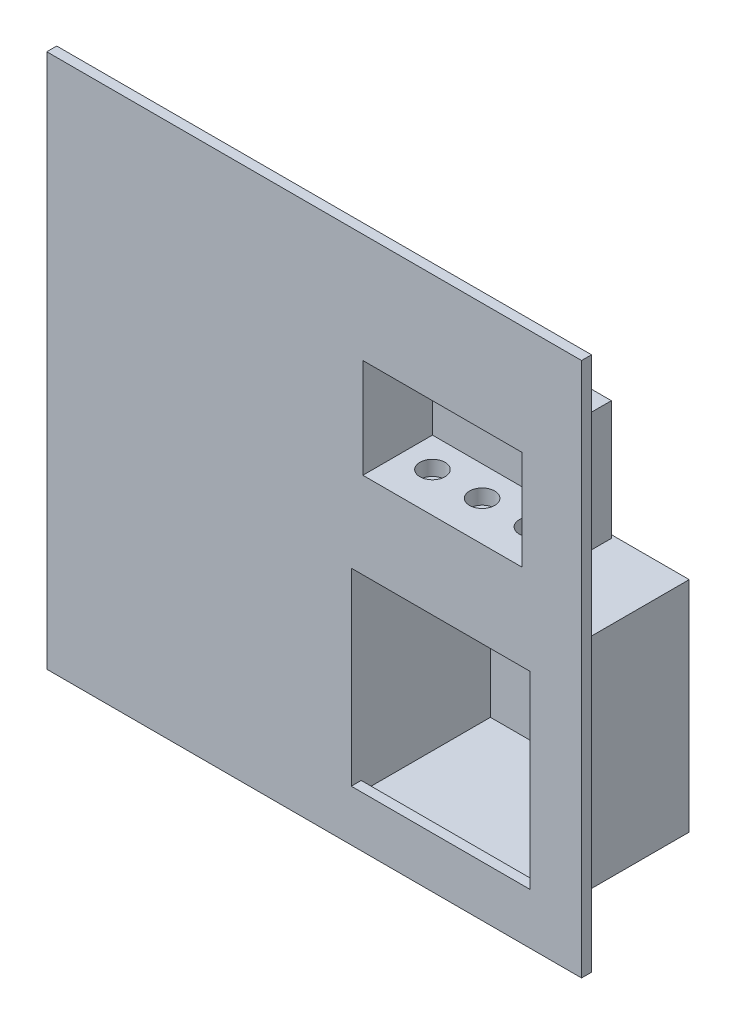
SolidWorks part; units mm, degrees
material "PE High Density Film"
ref_plane "Front Plane" through (0, 0, 0) normal (0, 0, 1) x (1, 0, 0)
ref_plane "Top Plane" through (0, 0, 0) normal (0, 1, 0) x (1, 0, 0)
ref_plane "Right Plane" through (0, 0, 0) normal (1, 0, 0) x (0, 0, -1)
sketch "Sketch1" plane through (0, 0, 0) normal (0, 0, 1) x (1, 0, 0)
  line L1 (0, 0) -> (683.26, 0)
  line L2 (0, 0) -> (0, 683.26)
  line L3 (0, 683.26) -> (683.26, 683.26)
  line L4 (683.26, 0) -> (683.26, 683.26)
  line L5 (403.86, 543.56) -> (607.06, 543.56)
  line L6 (403.86, 543.56) -> (403.86, 416.56)
  line L7 (403.86, 416.56) -> (607.06, 416.56)
  line L8 (607.06, 543.56) -> (607.06, 416.56)
  point P9 (607.06, 480.06)
  dimension "D1" = 683.26
  dimension "D2" = 76.2
  dimension "D3" = 203.2
  dimension "D4" = 127
  dimension "D5" = 203.2
extrude "Boss-Extrude1" add sketch "Sketch1" along normal blind 12.7
sketch "Sketch2" plane through (0, 416.56, 0) normal (0, 1, 0) x (1, 0, 0)
  line L1 (403.86, 0) -> (607.06, 0)
  line L2 (403.86, 0) -> (403.86, 76.2)
  line L3 (403.86, 76.2) -> (607.06, 76.2)
  line L4 (607.06, 0) -> (607.06, 76.2)
  dimension "D1" = 76.2
extrude "Boss-Extrude2" add sketch "Sketch2" against normal blind 25.4
sketch "Sketch3" plane through (0, 416.56, 0) normal (0, 1, 0) x (1, 0, 0)
  line L6 (607.06, -12.7) -> (607.06, 0)
  line L7 (607.06, 0) -> (607.06, 76.2)
  line L8 (607.06, 76.2) -> (403.86, 76.2)
  line L9 (403.86, 76.2) -> (403.86, 0)
  line L10 (403.86, 0) -> (403.86, -12.7)
  line L11 (403.86, -12.7) -> (607.06, -12.7)
  line L12 (607.06, -12.7) -> (607.06, 0)
  line L13 (607.06, 0) -> (607.06, 76.2)
  line L14 (607.06, 76.2) -> (403.86, 76.2)
  line L15 (403.86, 76.2) -> (403.86, 0)
  line L16 (403.86, 0) -> (403.86, -12.7)
  line L17 (403.86, -12.7) -> (607.06, -12.7)
  circle A1 centre (441.96, 38.1) radius 16.0655
  circle A2 centre (505.46, 38.1) radius 16.0655
  circle A3 centre (568.96, 38.1) radius 16.0655
  point P6 (403.86, 38.1)
  dimension "D2" = 32.131
  dimension "D4" = 32.131
  dimension "D5" = 32.131
  dimension "D3" = 38.1
  dimension "D6" = 63.5
  dimension "D7" = 63.5
  dimension "D1" = 0
extrude "Cut-Extrude1" cut sketch "Sketch3" against normal blind 19.05 contours A3 | A2 | A1
sketch "Sketch4" plane through (0, 0, 0) normal (0, 0, -1) x (-1, 0, 0)
  line L0 (-607.06, 416.56) -> (-403.86, 416.56) construction
  line L1 (-607.06, 416.56) -> (-619.76, 416.56)
  line L2 (-607.06, 416.56) -> (-607.06, 543.56)
  line L3 (-607.06, 543.56) -> (-619.76, 543.56)
  line L4 (-619.76, 416.56) -> (-619.76, 543.56)
  line L5 (-607.06, 543.56) -> (-403.86, 543.56)
  line L6 (-607.06, 543.56) -> (-607.06, 556.26)
  line L7 (-607.06, 556.26) -> (-403.86, 556.26)
  line L8 (-403.86, 543.56) -> (-403.86, 556.26)
  line L9 (-403.86, 543.56) -> (-391.16, 543.56)
  line L10 (-403.86, 543.56) -> (-403.86, 416.56)
  line L11 (-403.86, 416.56) -> (-391.16, 416.56)
  line L12 (-391.16, 543.56) -> (-391.16, 416.56)
  line L13 (-403.86, 543.56) -> (-403.86, 416.56) construction
  line L15 (-607.06, 543.56) -> (-403.86, 543.56) construction
  line L16 (-607.06, 543.56) -> (-619.76, 543.56)
  line L17 (-607.06, 543.56) -> (-607.06, 556.26)
  line L18 (-607.06, 556.26) -> (-619.76, 556.26)
  line L19 (-619.76, 543.56) -> (-619.76, 556.26)
  line L20 (-403.86, 543.56) -> (-391.16, 543.56)
  line L21 (-403.86, 543.56) -> (-403.86, 556.26)
  line L22 (-403.86, 556.26) -> (-391.16, 556.26)
  line L23 (-391.16, 543.56) -> (-391.16, 556.26)
  line L24 (-607.06, 416.56) -> (-619.76, 416.56)
  line L25 (-607.06, 416.56) -> (-607.06, 403.86)
  line L26 (-607.06, 403.86) -> (-619.76, 403.86)
  line L27 (-619.76, 416.56) -> (-619.76, 403.86)
  line L28 (-403.86, 416.56) -> (-391.16, 416.56)
  line L29 (-403.86, 416.56) -> (-403.86, 403.86)
  line L30 (-403.86, 403.86) -> (-391.16, 403.86)
  line L31 (-391.16, 416.56) -> (-391.16, 403.86)
  line M7 (-403.86, 416.56) -> (-403.86, 391.16)
  line M9 (-607.06, 391.16) -> (-607.06, 416.56)
  line M10 (-607.06, 416.56) -> (-607.06, 543.56)
  line M11 (-607.06, 543.56) -> (-403.86, 543.56)
  line M12 (-403.86, 543.56) -> (-403.86, 416.56)
  dimension "D1" = 12.7
  dimension "D2" = 12.7
  dimension "D3" = 12.7
extrude "Boss-Extrude4" add sketch "Sketch4" along normal up to surface (76.2 mm away) contours L1 L27 L26 M9 | L4 L1 L3 M10 | L8 L7 L6 M11 | L19 L3 L6 L18 | L9 L23 L22 L8 | L12 L9 L11 M12 | L31 L11 L30 M7 up to face at (505.46, 403.86, -76.2)
sketch "Sketch5" plane through (0, 0, -76.2) normal (0, 0, -1) x (-1, 0, 0)
  line L4 (-607.06, 391.16) -> (-403.86, 391.16)
  line L5 (-391.16, 403.86) -> (-391.16, 556.26)
  line L6 (-391.16, 556.26) -> (-619.76, 556.26)
  line L7 (-619.76, 556.26) -> (-619.76, 403.86)
  line L8 (-607.06, 391.16) -> (-403.86, 391.16)
  line L9 (-391.16, 403.86) -> (-391.16, 556.26)
  line L10 (-391.16, 556.26) -> (-619.76, 556.26)
  line L11 (-619.76, 556.26) -> (-619.76, 403.86)
  line L16 (-403.86, 391.16) -> (-403.86, 403.86)
  line L17 (-403.86, 391.16) -> (-403.86, 403.86)
  line L18 (-403.86, 403.86) -> (-391.16, 403.86)
  line L19 (-403.86, 403.86) -> (-391.16, 403.86)
  line L20 (-619.76, 403.86) -> (-607.06, 403.86)
  line L21 (-619.76, 403.86) -> (-607.06, 403.86)
  line L22 (-607.06, 403.86) -> (-607.06, 391.16)
  line L23 (-607.06, 403.86) -> (-607.06, 391.16)
  dimension "D1" = 0
extrude "Boss-Extrude5" add sketch "Sketch5" along normal blind 12.7
sketch "Sketch6" plane through (0, 0, 12.7) normal (0, 0, 1) x (1, 0, 0)
  line L1 (389.0156, 306.3991) -> (617.6156, 306.3991)
  line L2 (389.0156, 306.3991) -> (389.0156, 52.3991)
  line L3 (389.0156, 52.3991) -> (617.6156, 52.3991)
  line L4 (617.6156, 306.3991) -> (617.6156, 52.3991)
  dimension "D1" = 254
  dimension "D2" = 228.6
extrude "Cut-Extrude2" cut sketch "Sketch6" against normal through all
sketch "Sketch7" plane through (0, 0, 0) normal (0, 0, -1) x (-1, 0, 0)
  line L1 (-617.6156, 52.3991) -> (-389.0156, 52.3991)
  line L2 (-617.6156, 52.3991) -> (-617.6156, 39.6991)
  line L3 (-617.6156, 39.6991) -> (-389.0156, 39.6991)
  line L4 (-389.0156, 52.3991) -> (-389.0156, 39.6991)
  dimension "D1" = 12.7
extrude "Boss-Extrude6" add sketch "Sketch7" along normal blind 177.8
ref_plane "Plane1" through (0, 179.3991, 0) normal (0, 1, 0) x (1, 0, 0)
mirror "Mirror1" about plane through (0, 179.3991, 0) normal (0, 1, 0) of "Boss-Extrude6"
sketch "Sketch8" plane through (0, 0, 0) normal (0, 0, -1) x (-1, 0, 0)
  line L5 (-617.6156, 319.0991) -> (-630.3156, 319.0991)
  line L6 (-617.6156, 319.0991) -> (-617.6156, 39.6991)
  line L7 (-617.6156, 39.6991) -> (-630.3156, 39.6991)
  line L8 (-630.3156, 319.0991) -> (-630.3156, 39.6991)
  line L9 (-389.0156, 319.0991) -> (-376.3156, 319.0991)
  line L10 (-389.0156, 319.0991) -> (-389.0156, 39.6991)
  line L11 (-389.0156, 39.6991) -> (-376.3156, 39.6991)
  line L12 (-376.3156, 319.0991) -> (-376.3156, 39.6991)
  dimension "D1" = 12.7
  dimension "D2" = 279.4
  dimension "D3" = 12.7
  dimension "D4" = 279.4
extrude "Boss-Extrude7" add sketch "Sketch8" along normal blind 177.8
sketch "Sketch9" plane through (0, 52.3991, 0) normal (0, 1, 0) x (1, 0, 0)
  line L0 (617.6156, 177.8) -> (617.6156, -12.7) construction
  line L1 (389.0156, 177.8) -> (617.6156, 177.8)
  line L2 (389.0156, 177.8) -> (389.0156, 165.1)
  line L3 (389.0156, 165.1) -> (617.6156, 165.1)
  line L4 (617.6156, 177.8) -> (617.6156, 165.1)
  dimension "D1" = 12.7
extrude "Boss-Extrude8" add sketch "Sketch9" along normal blind 254
sketch "Sketch10" plane through (0, 52.3991, 0) normal (0, 1, 0) x (1, 0, 0)
  line L0 (617.6156, 165.1) -> (617.6156, -12.7) construction
  line L1 (389.0156, -12.7) -> (617.6156, -12.7)
  line L2 (389.0156, -12.7) -> (389.0156, 0)
  line L3 (389.0156, 0) -> (617.6156, 0)
  line L4 (617.6156, -12.7) -> (617.6156, 0)
  dimension "D1" = 12.7
extrude "Boss-Extrude9" add sketch "Sketch10" along normal blind 12.7
